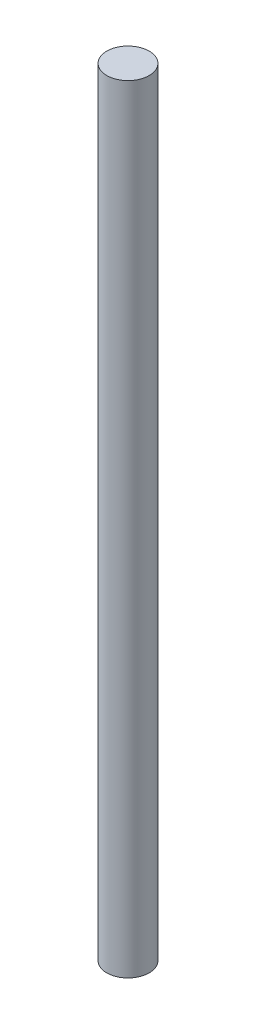
SolidWorks part; units mm, degrees
ref_plane "Front Plane" through (0, 0, 0) normal (0, 0, 1) x (1, 0, 0)
ref_plane "Top Plane" through (0, 0, 0) normal (0, 1, 0) x (1, 0, 0)
ref_plane "Right Plane" through (0, 0, 0) normal (1, 0, 0) x (0, 0, -1)
sketch "Sketch1" plane through (0, 0, 0) normal (0, 1, 0) x (1, 0, 0)
  circle A0 centre (0, 0) radius 6
  dimension "D1" = 12
extrude "Boss-Extrude1" add sketch "Sketch1" along normal blind 220
